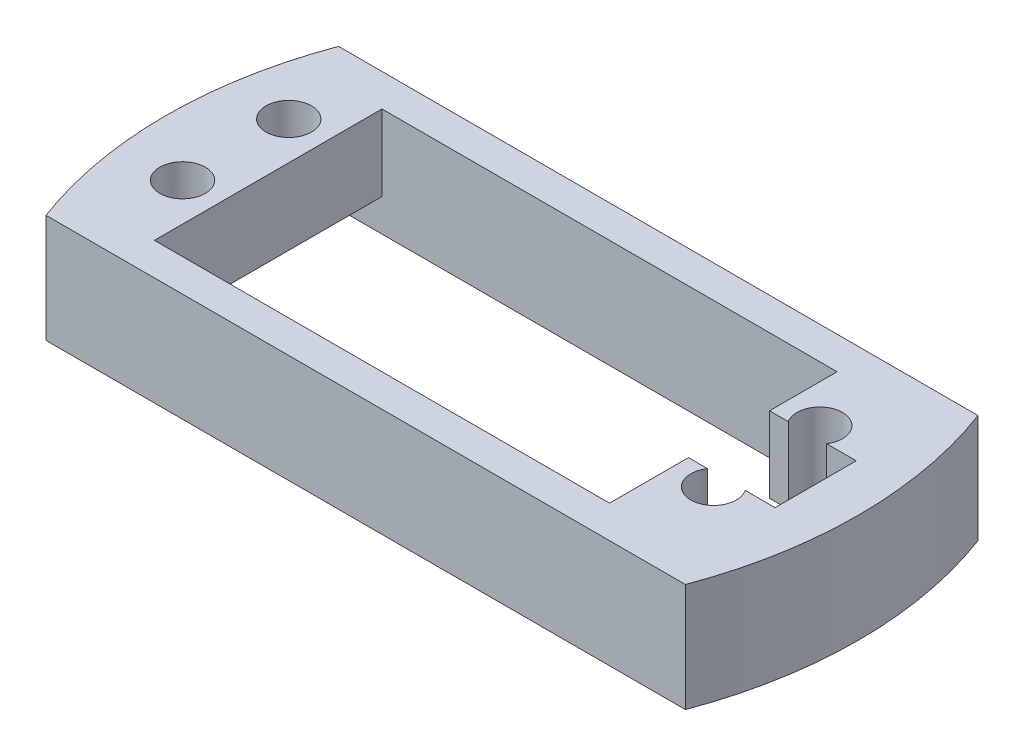
SolidWorks part; units mm, degrees
ref_plane "Front Plane" through (0, 0, 0) normal (0, 0, 1) x (1, 0, 0)
ref_plane "Top Plane" through (0, 0, 0) normal (0, 1, 0) x (1, 0, 0)
ref_plane "Right Plane" through (0, 0, 0) normal (1, 0, 0) x (0, 0, -1)
sketch "Sketch1" plane through (0, 0, 0) normal (0, 1, 0) x (1, 0, 0)
  line L0 (-37, 14.159) -> (22, 14.159)
  line L1 (-37, -12.841) -> (22, -12.841)
  line L2 (-9, 11.159) -> (-9, -14.659) construction
  line L3 (-30, 11.159) -> (12, 11.159)
  line L4 (-30, 11.159) -> (-30, -9.841)
  line L5 (-30, -9.841) -> (12, -9.841)
  line L6 (12, 11.159) -> (12, -9.841)
  arc A0 (-37, 14.159) -> (-37, -12.841) centre (-0.9445, 0.659) ccw
  arc A1 (22, 14.159) -> (22, -12.841) centre (-14.0555, 0.659) cw
  circle A2 centre (15.5, 6.059) radius 2.1
  circle A3 centre (15.5, -3.741) radius 2.1
  circle A4 centre (-33.5, 6.059) radius 2.1
  circle A5 centre (-33.5, -3.741) radius 2.1
  point P4 (0, 1.159)
  dimension "D3" = 4.2
  dimension "D12" = 10
  dimension "D14" = 7
  dimension "D1" = 21
  dimension "D2" = 42
  dimension "D4" = 4.9
  dimension "D5" = 4.9
  dimension "D6" = 10
  dimension "D7" = 12
  dimension "D8" = 3.5
  dimension "D9" = 0
  dimension "D10" = 3
  dimension "D11" = 3
  dimension "D13" = 10
  dimension "D15" = 7
extrude "Boss-Extrude1" add sketch "Sketch1" along normal blind 10
sketch "Sketch2" plane through (0, 0, 0) normal (0, 1, 0) x (1, 0, 0)
  line L0 (12, -9.841) -> (12, 11.159) construction
  line L1 (12, 4.9238) -> (20, 4.9238)
  line L2 (12, 4.9238) -> (12, -2.5619)
  line L3 (12, -2.5619) -> (20, -2.5619)
  line L4 (20, 4.9238) -> (20, -2.5619)
  dimension "D1" = 8
extrude "Cut-Extrude1" cut sketch "Sketch2" along normal blind 10
sketch "Sketch3" plane through (0, 0, 0) normal (0, 1, 0) x (1, 0, 0)
  line L0 (-30, 11.159) -> (-37.5774, 11.159)
  line L2 (-30, 11.159) -> (-30, -9.841)
  line L5 (12, 11.159) -> (19.9258, 11.159)
  line L6 (12, 11.159) -> (12, -9.8178)
  line L7 (12, -9.8178) -> (19.9258, -9.8178)
  line L8 (19.9258, 11.159) -> (19.9258, -9.8178)
  line L9 (-37.5774, 11.159) -> (-37.5774, -9.841)
  line L10 (-37.5774, -9.841) -> (-30, -9.841)
extrude "Cut-Extrude3" cut sketch "Sketch3" along normal blind 3
